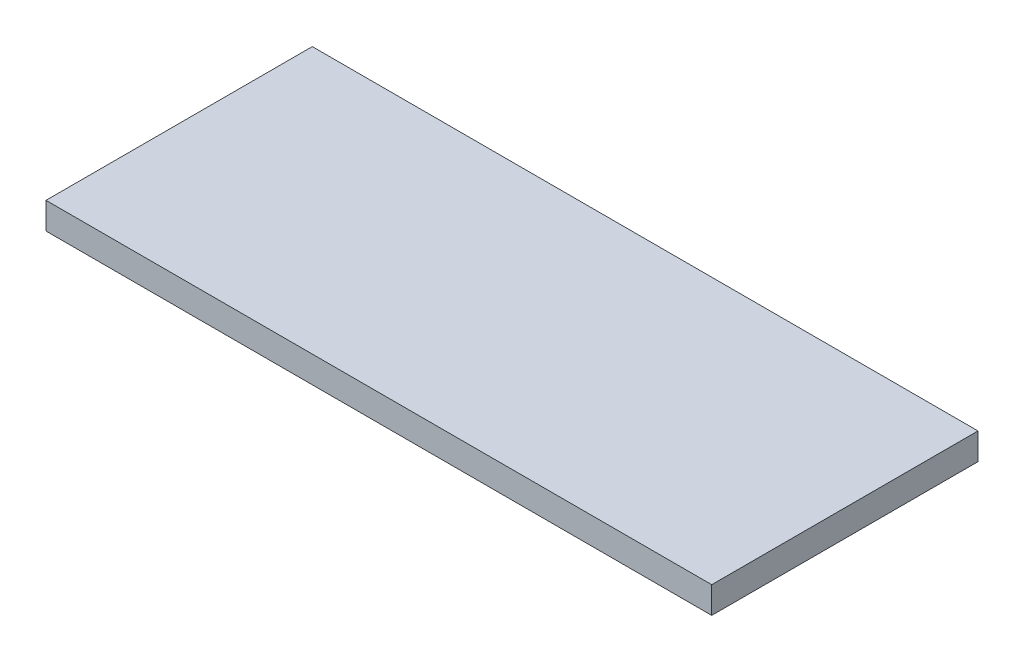
SolidWorks part; units mm, degrees
ref_plane "Front Plane" through (0, 0, 0) normal (0, 0, 1) x (1, 0, 0)
ref_plane "Top Plane" through (0, 0, 0) normal (0, 1, 0) x (1, 0, 0)
ref_plane "Right Plane" through (0, 0, 0) normal (1, 0, 0) x (0, 0, -1)
other "Configuration Table"
sketch "Sketch1" plane through (0, 0, 0) normal (0, 0, 1) x (1, 0, 0)
  line L1 (100, 780) -> (600, 780)
  line L2 (100, 780) -> (100, 800)
  line L3 (100, 800) -> (600, 800)
  line L4 (600, 780) -> (600, 800)
extrude "OVEN_kesme_ust_travers_1" add sketch "Sketch1" against normal blind 200 from offset 200 separate body
